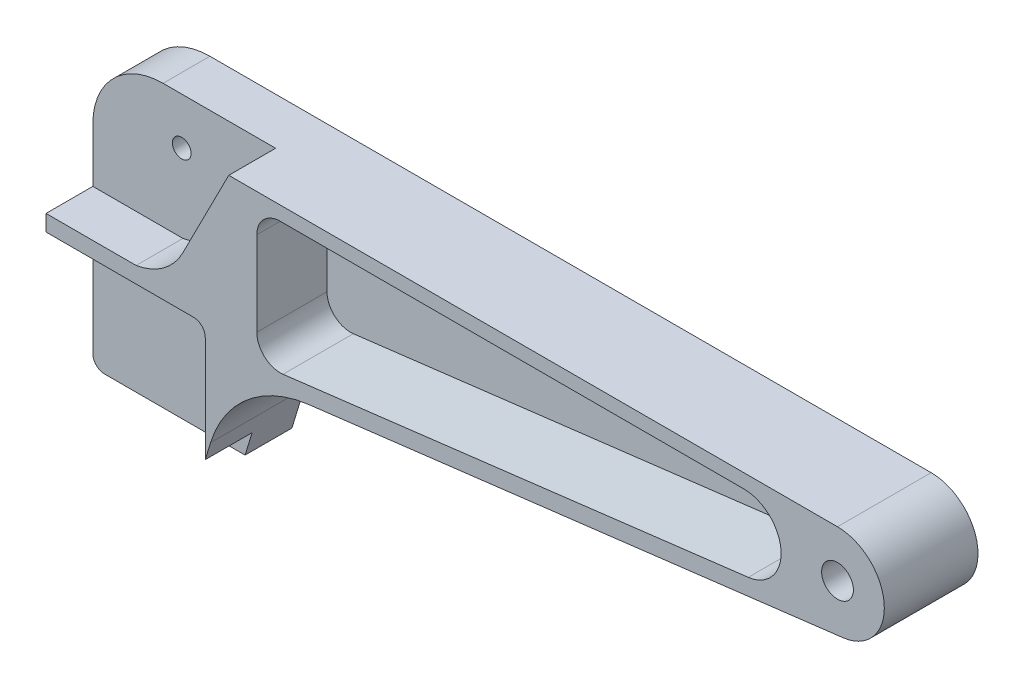
SolidWorks part; units mm, degrees
ref_plane "正面" through (0, 0, 0) normal (0, 0, 1) x (1, 0, 0)
ref_plane "平面" through (0, 0, 0) normal (0, 1, 0) x (1, 0, 0)
ref_plane "右側面" through (0, 0, 0) normal (1, 0, 0) x (0, 0, -1)
sketch "ｽｹｯﾁ1" plane through (0, 0, 0) normal (0, 0, 1) x (1, 0, 0)
  line L0 (0, 0) -> (337.955, 0)
  line L1 (339.8971, -39.9055) -> (79.7825, -71.6573)
  line L2 (79.7825, -71.6573) -> (65, -120)
  line L3 (65, -120) -> (0, -120)
  line L4 (0, -120) -> (0, 0)
  line L5 (337.955, -20) -> (0, -20) construction
  arc A0 (337.955, 0) -> (339.8971, -39.9055) centre (337.955, -20) cw
  circle A1 centre (337.955, -20) radius 6.7919
  circle A2 centre (37.955, -20) radius 3.9953
  dimension "D1" = 300
  dimension "D2" = 20
  dimension "D3" = 120
  dimension "D4" = 65
extrude "ﾎﾞｽ - 押し出し1" add sketch "ｽｹｯﾁ1" along normal blind 40
sketch "ｽｹｯﾁ2" plane through (0, 0, 40) normal (0, 0, 1) x (1, 0, 0)
  line L0 (100, -6) -> (297.955, -6)
  line L1 (299.8849, -37.7378) -> (101.2117, -61.9895)
  line L2 (90, -52.0632) -> (90, -16)
  line L4 (0, 0) -> (0, -120) construction
  line L5 (79.7825, -71.6573) -> (339.8971, -39.9055) construction
  line L6 (337.955, 0) -> (0, 0) construction
  arc A0 (297.955, -6) -> (299.8849, -37.7378) centre (297.955, -21.9276) cw
  circle A1 centre (337.955, -20) radius 6.7919 construction
  arc A2 (90, -16) -> (100, -6) centre (100, -16) cw
  arc A3 (101.2117, -61.9895) -> (90, -52.0632) centre (100, -52.0632) cw
  point P4 (0, 0)
  point P8 (254.4585, 2.407)
  dimension "D5" = 10
  dimension "D1" = 6
  dimension "D2" = 7
  dimension "D3" = 40
  dimension "D4" = 90
extrude "ｶｯﾄ - 押し出し1" cut sketch "ｽｹｯﾁ2" against normal blind 30
fillet "ﾌｨﾚｯﾄ1" radius 50 1 edges at (79.7825, -71.6573, 20)
sketch "ｽｹｯﾁ3" plane through (0, 0, 40) normal (0, 0, 1) x (1, 0, 0)
  line L0 (0, -60) -> (68, -60)
  line L1 (0, 0) -> (0, -120) construction
  line L2 (68, -60) -> (68, -120)
  line L3 (68, -120) -> (0, -120)
  line L4 (0, -120) -> (0, -60)
  line L6 (337.955, 0) -> (0, 0) construction
  line L7 (0, -120) -> (65, -120) construction
  point P5 (70.2484, -59.6598)
  dimension "D1" = 68
  dimension "D2" = 60
extrude "ｶｯﾄ - 押し出し2" cut sketch "ｽｹｯﾁ3" against normal blind 20
fillet "ﾌｨﾚｯﾄ2" radius 30 1 edges at (0, 0, 20)
fillet "ﾌｨﾚｯﾄ3" radius 5 1 edges at (68, -60, 30)
fillet "ﾌｨﾚｯﾄ4" radius 5 1 edges at (0, -120, 10)
sketch "ｽｹｯﾁ4" plane through (0, 0, 40) normal (0, 0, 1) x (1, 0, 0)
  line L0 (78.037, 0) -> (58.3553, -38.5768)
  line L1 (337.955, 0) -> (30, 0) construction
  line L2 (38.4763, -53.1138) -> (0, -53.1138)
  line L3 (0, -30) -> (0, -60) construction
  line L4 (78.037, 0) -> (0, 0)
  line L5 (0, 0) -> (0, -53.1138)
  arc A0 (58.3553, -38.5768) -> (38.4763, -53.1138) centre (34.0218, -26.1619) cw
extrude "ｶｯﾄ - 押し出し3" cut sketch "ｽｹｯﾁ4" against normal blind 20
